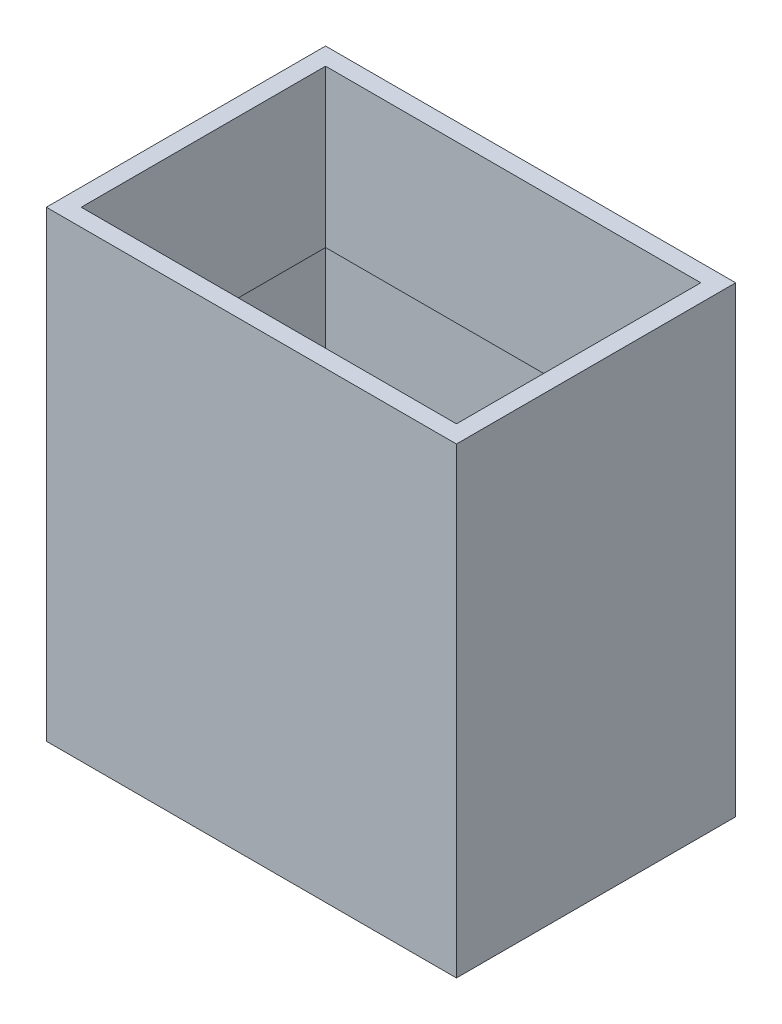
SolidWorks part; units mm, degrees
ref_plane "Front Plane" through (0, 0, 0) normal (0, 0, 1) x (1, 0, 0)
ref_plane "Top Plane" through (0, 0, 0) normal (0, 1, 0) x (1, 0, 0)
ref_plane "Right Plane" through (0, 0, 0) normal (1, 0, 0) x (0, 0, -1)
sketch "Sketch1" plane through (0, 0, 0) normal (0, 1, 0) x (1, 0, 0)
  line L0 (0, 16) -> (47, 16) construction
  line L1 (0, 0) -> (47, 0)
  line L2 (0, 0) -> (0, 32)
  line L3 (0, 32) -> (47, 32)
  line L4 (47, 0) -> (47, 32)
  line L5 (2, 2) -> (45, 2)
  line L6 (2, 2) -> (2, 30)
  line L7 (2, 30) -> (45, 30)
  line L8 (45, 2) -> (45, 30)
  line L9 (23.5, 0) -> (23.5, 32) construction
  line L10 (2, 30) -> (45, 2) construction
  line L11 (2, 2) -> (45, 30) construction
  point P13 (23.5, 16)
  point P14 (23.5, 16)
  dimension "D1" = 43
  dimension "D2" = 28
  dimension "D3" = 2
  dimension "D4" = 2
extrude "Boss-Extrude1" add sketch "Sketch1" along normal blind 28
sketch "Sketch2" plane through (0, 0, 0) normal (0, -1, 0) x (1, 0, 0)
  line L1 (1.5, -30.5) -> (45.5, -30.5)
  line L2 (1.5, -30.5) -> (1.5, -1.5)
  line L3 (1.5, -1.5) -> (45.5, -1.5)
  line L4 (45.5, -30.5) -> (45.5, -1.5)
  line L5 (3.5, -3.5) -> (3.5, -1.5) construction
  line L6 (3.5, -3.5) -> (1.5, -3.5) construction
  line L7 (43.5, -3.5) -> (45.5, -3.5) construction
  line L8 (43.5, -28.5) -> (43.5, -30.5) construction
  line L11 (2, -30) -> (2, -2) construction
  point P4 (3.5, -3.5)
  point P5 (43.5, -28.5)
  point P16 (2, -2)
  point P17 (3.8265, -3.5)
  point P18 (2.8367, -2.6912)
  point P19 (45, -2)
  point P20 (3.5, -3.5)
  point P21 (1.4817, -3.5)
  point P22 (43.5, -3.5)
  point P23 (0, 0)
  point P24 (0, 0)
  point P26 (3.5, -3.5)
  point P27 (3.5, -3.5)
  dimension "D1" = 2
  dimension "D2" = 0.5
extrude "Cut-Extrude1" cut sketch "Sketch2" against normal blind 10
sketch "Sketch3" plane through (0, 0, 0) normal (0, -1, 0) x (1, 0, 0)
  line L0 (0, 0) -> (0, -32) construction
  line L1 (0, -32) -> (47, -32)
  line L2 (0, -32) -> (0, 0)
  line L3 (0, 0) -> (47, 0)
  line L4 (47, -32) -> (47, 0)
  line L5 (1.5, -30.5) -> (45.5, -30.5)
  line L6 (1.5, -30.5) -> (1.5, -1.5)
  line L7 (1.5, -1.5) -> (45.5, -1.5)
  line L8 (45.5, -30.5) -> (45.5, -1.5)
  line L9 (0, 0) -> (47, 0) construction
  line L10 (47, 0) -> (47, -32) construction
  line L11 (0, -32) -> (0, 0) construction
  line L14 (47, -32) -> (0, -32) construction
  point P6 (46, 0)
  point P10 (0, 0)
  point P11 (-0.7262, 0)
  point P13 (47, -32)
  point P14 (2, -2)
  point P16 (44, -29)
  point P18 (46, -31)
  point P20 (0, 0)
  point P22 (0, -31)
  point P25 (0, 0)
  point P27 (0, -32)
  point P32 (1.5, -1.5)
  point P34 (45.5, -30.5)
extrude "Boss-Extrude2" add sketch "Sketch3" along normal blind 25
sketch "Sketch4" plane through (0, -25, 0) normal (0, -1, 0) x (1, 0, 0)
  line L0 (0, -16) -> (47, -16) construction
  line L1 (0, -32) -> (47, -32)
  line L2 (0, -32) -> (0, 0)
  line L3 (0, 0) -> (47, 0)
  line L4 (47, -32) -> (47, 0)
  line L5 (0, 0) -> (0, -32) construction
  line L6 (0, -32) -> (47, -32) construction
  circle A0 centre (23.5, -16) radius 6.5
  point P8 (3, -3)
  point P9 (0, -32)
  point P16 (47, 0)
  dimension "D1" = 13
extrude "Boss-Extrude3" add sketch "Sketch4" against normal blind 3
sketch "Sketch5" plane through (0, -25, 0) normal (0, -1, 0) x (1, 0, 0)
  circle A0 centre (10, -16) radius 2.65 construction
  circle A1 centre (10, -16) radius 2.65 construction
  circle A2 centre (37, -16) radius 2.65 construction
  circle A3 centre (37, -16) radius 2.65 construction
  circle A4 centre (10, -16) radius 4
  circle A5 centre (37, -16) radius 4
  circle A6 centre (10, -16) radius 5
  circle A7 centre (37, -16) radius 5
  dimension "D1" = 10
  dimension "D2" = 8
  dimension "D3" = 8
extrude "Boss-Extrude4" add sketch "Sketch5" against normal blind 5
sketch "Sketch6" plane through (0, -25, 0) normal (0, -1, 0) x (1, 0, 0)
  circle A0 centre (10, -16) radius 2.65
  circle A1 centre (10, -16) radius 2.65 construction
  circle A2 centre (37, -16) radius 2.65
  circle A3 centre (37, -16) radius 2.65 construction
  point P7 (37, -16)
extrude "Boss-Extrude5" add sketch "Sketch6" against normal blind 5
